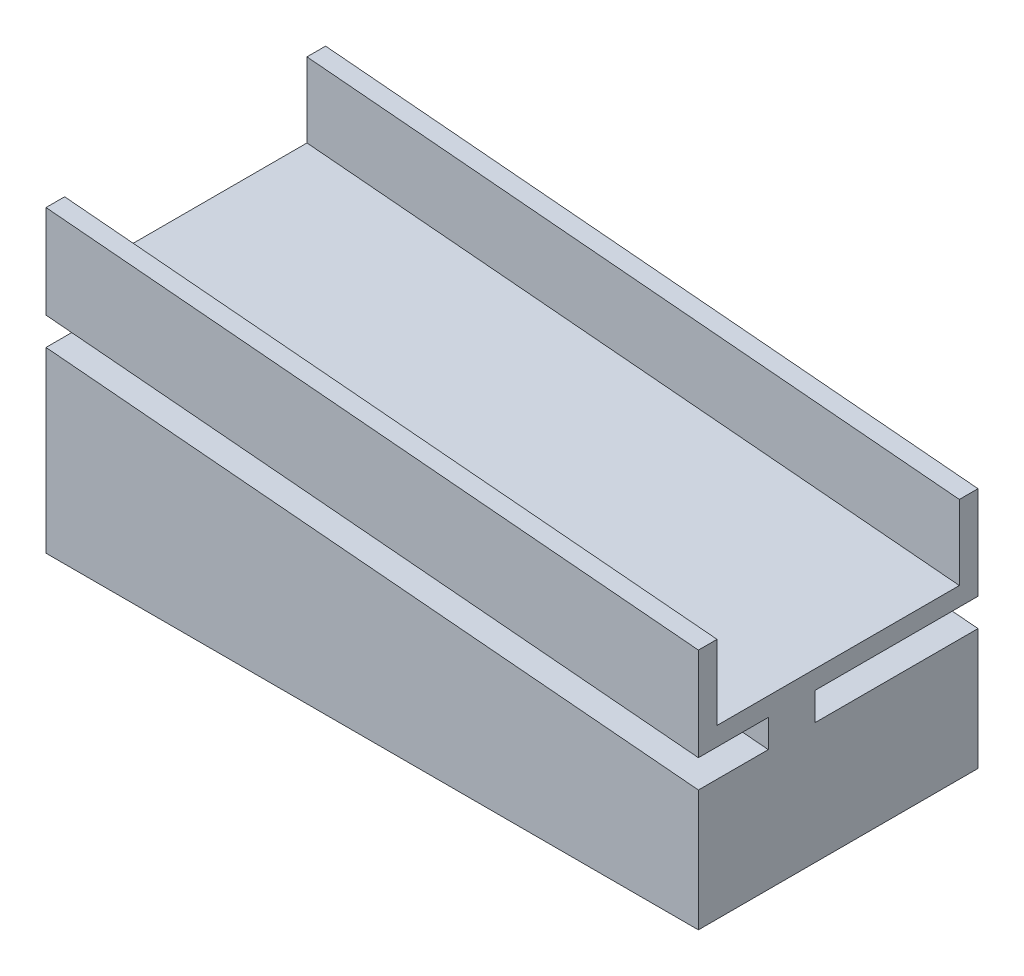
SolidWorks part; units mm, degrees
ref_plane "Alzado" through (0, 0, 0) normal (0, 0, 1) x (1, 0, 0)
ref_plane "Planta" through (0, 0, 0) normal (0, 1, 0) x (1, 0, 0)
ref_plane "Vista lateral" through (0, 0, 0) normal (1, 0, 0) x (0, 0, -1)
sketch "Croquis1" plane through (0, 0, 0) normal (0, 0, 1) x (1, 0, 0)
  line L0 (0, 0) -> (0, 19.1242)
  line L1 (0, 19.1242) -> (70, 13)
  line L2 (70, 13) -> (70, 0)
  line L3 (70, 0) -> (0, 0)
  line L4 (70, 13) -> (-25.8453, 13) construction
  dimension "D1" = 70
  dimension "D2" = 5
  dimension "D3" = 13
extrude "Saliente-Extruir1" add sketch "Croquis1" along normal blind 30
ref_plane "Plano1" through (0, 0, 20) normal (0, 0, 1) x (1, 0, 0)
sketch "Croquis3" plane through (0, 0, 20) normal (0, 0, 1) x (1, 0, 0)
  line L0 (0, 19.1242) -> (70, 13)
  line L1 (70, 13) -> (70, 16)
  line L2 (70, 16) -> (0, 22.1242)
  line L3 (0, 22.1242) -> (0, 19.1242)
  dimension "D1" = 3
extrude "Saliente-Extruir2" add sketch "Croquis3" along normal mid plane 5
sketch "Croquis4" plane through (0, 0, 20) normal (0, 0, 1) x (1, 0, 0)
  line L0 (0, 22.1242) -> (70, 16)
sketch "Croquis5" plane through (0, 0, 0) normal (-1, 0, 0) x (0, 0, 1)
  line L0 (28, 32.1242) -> (30, 32.1242)
  line L1 (0, 22.1242) -> (30, 22.1242)
  line L2 (0, 22.1242) -> (0, 32.1242)
  line L3 (0, 32.1242) -> (2, 32.1242)
  line L4 (30, 22.1242) -> (30, 32.1242)
  line L6 (2, 32.1242) -> (2, 24.1242)
  line L7 (2, 24.1242) -> (28, 24.1242)
  line L8 (28, 32.1242) -> (28, 24.1242)
  line L9 (0, 22.1242) -> (30, 22.1242) construction
  dimension "D1" = 2
  dimension "D2" = 2
  dimension "D3" = 2
  dimension "D4" = 30
  dimension "D5" = 10
sweep "Barrer1" add profiles "Croquis5" path "Croquis4"
